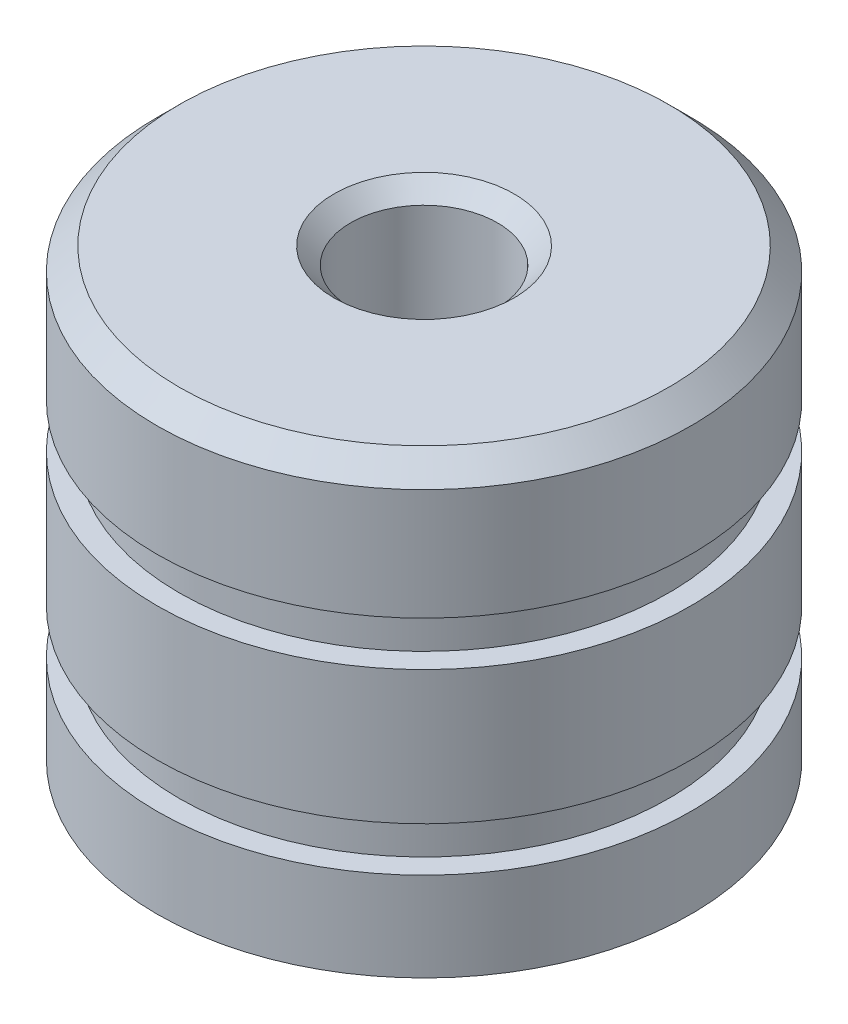
SolidWorks part; units mm, degrees
material "Alloy Steel"
ref_plane "Front Plane" through (0, 0, 0) normal (0, 0, 1) x (1, 0, 0)
ref_plane "Top Plane" through (0, 0, 0) normal (0, 1, 0) x (1, 0, 0)
ref_plane "Right Plane" through (0, 0, 0) normal (1, 0, 0) x (0, 0, -1)
sketch "Sketch2" plane through (0, 0, 0) normal (0, 1, 0) x (1, 0, 0)
  circle A0 centre (0, 0) radius 6
  dimension "D1" = 12
extrude "Boss-Extrude1" add sketch "Sketch2" along normal mid plane 10
chamfer "Chamfer1" distance 0.5 angle 45 1 edges at (0, 5, 6)
sketch "Sketch3" plane through (0, 0, 0) normal (1, 0, 0) x (0, 0, -1)
  line L0 (0, 8.1505) -> (0, -7.4642) construction
  line L1 (6, -5) -> (6, 4.5) construction
  line L2 (5.5, 2) -> (6, 2)
  line L3 (5.5, 2) -> (5.5, 1)
  line L4 (5.5, 1) -> (6, 1)
  line L6 (6, -2) -> (6, -3)
  line L8 (-6, 4.5) -> (6, 4.5) construction
  line L9 (5.5, -2) -> (6, -2)
  line L10 (5.5, -2) -> (5.5, -3)
  line L11 (5.5, -3) -> (6, -3)
  line L15 (6, 2) -> (6, 1)
  point P3 (6, 1.5)
  point P10 (6, -2.5)
  dimension "D1" = 1
  dimension "D2" = 1
  dimension "D3" = 2.5
  dimension "D4" = 3
  dimension "D5" = 0.5
  dimension "D6" = 0.5
  dimension "D7" = 6
revolve "Cut-Revolve1" cut sketch "Sketch3" angle 360 about L0
hole_wizard "M4 Tapped Hole1" positions "Sketch4" profile "Sketch5" tap size "M4" standard "ISO"
sketch "Sketch4" plane through (0, 5, 0) normal (0, 1, 0) x (1, 0, 0)
  point P0 (0, 0)
sketch "Sketch5" plane through (0, 5, 0) normal (1, 0, 0) x (0, 0, 1)
  line L0 (0, 0) -> (0, 8.9914)
  line L1 (0, 8.9914) -> (1.65, 8)
  line L2 (1.65, 8) -> (1.65, 0.375)
  line L3 (1.65, 0.375) -> (2.025, 0)
  line L5 (2.025, 0) -> (0, 0)
  line L6 (-1.65, 0.375) -> (-2.025, 0) construction
  line L10 (0, 8.9914) -> (-1.65, 8) construction
  line L11 (0, -6.35) -> (0, 107.95) construction
  dimension "Tap Drill Dia." = 3.3
  dimension "Tap Drill Depth" = 8
  dimension "Near C'Sink Dia." = 4.05
  dimension "Near C'Sink Angle" = 90
  dimension "Drill Angle" = 118
cosmetic thread "Hole Thread1" parameters "D1"=8, "D2"=4
